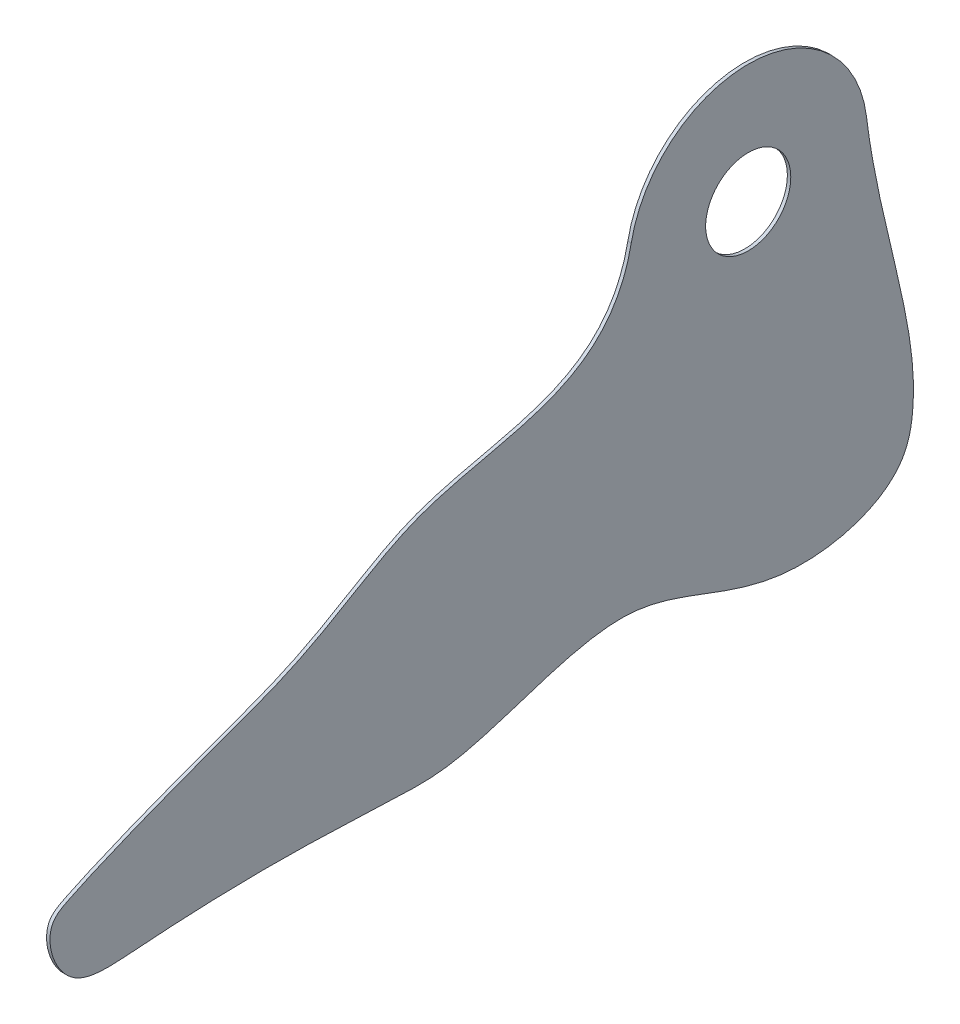
SolidWorks part; units mm, degrees
material "Teras S325"
ref_plane "Front Plane" through (0, 0, 0) normal (0, 0, 1) x (1, 0, 0)
ref_plane "Top Plane" through (0, 0, 0) normal (0, 1, 0) x (1, 0, 0)
ref_plane "Right Plane" through (0, 0, 0) normal (1, 0, 0) x (0, 0, -1)
sketch "Sketch3" plane through (0, 0, 0) normal (1, 0, 0) x (0, 0, -1)
  line L0 (0, 55) -> (0, -55) construction
  line L1 (55, 0) -> (-55, 0) construction
  line L2 (0, 100) -> (0, 29.0992) construction
  circle A0 centre (0, 100) radius 12.5
  arc A1 (34.7369, 104.2833) -> (-34.3532, 106.6975) centre (0, 100) ccw
  spline S0 degree 3 poles (-34.3532, 106.6975) (-36.339, 96.5121) (-50.9488, 74.621) (-85.7262, 74.2719) (-114.84, 59.5286) (-128.7221, 49.7184) (-165.2989, 36.5654) (-189.6537, 27.3204) (-207.9029, 18.0467) (-201.4231, -2.0483) (-146.5939, 2.6415) (-120.1446, 0.6415) (-77.9922, -0.701) (-34.702, 23.728) (4.0979, -6.3572) (45.1754, 4.4646) (52.1066, 40.3815) (38.6786, 72.3432) (34.7369, 104.2833) knots 0 0 0 0 0.054541 0.168814 0.190562 0.262972 0.282353 0.364989 0.379148 0.409787 0.430597 0.56644 0.595187 0.701095 0.796074 0.860424 0.880816 1 1 1 1
  dimension "D1" = 25
  dimension "D2" = 100
  dimension "D3" = 70
extrude "Extrude1" add sketch "Sketch3" along normal mid plane 1
